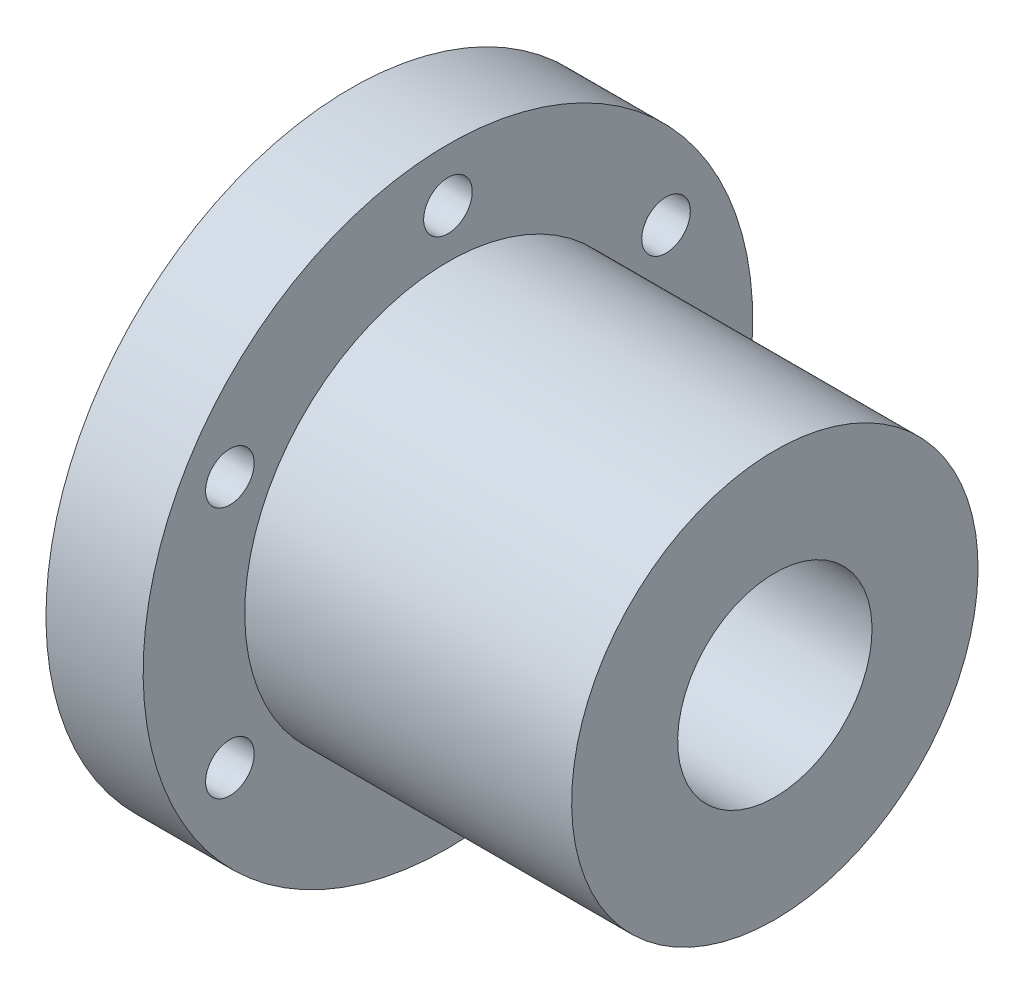
SolidWorks part; units mm, degrees
material "1.0037 (S235JR)"
ref_plane "Front Plane" through (0, 0, 0) normal (0, 0, 1) x (1, 0, 0)
ref_plane "Top Plane" through (0, 0, 0) normal (0, 1, 0) x (1, 0, 0)
ref_plane "Right Plane" through (0, 0, 0) normal (1, 0, 0) x (0, 0, -1)
sketch "Sketch1" plane through (0, 0, 0) normal (0, 0, 1) x (1, 0, 0)
  line L0 (-24, 34.5) -> (-13, 34.5)
  line L1 (-13, 34.5) -> (-13, 23)
  line L3 (24, 23) -> (24, 11)
  line L4 (24, 11) -> (-24, 11)
  line L5 (-24, 11) -> (-24, 34.5)
  line L9 (-13, 23) -> (24, 23)
  line L10 (-82.106, 0) -> (82.106, 0) construction
  point P12 (0, 11)
  dimension "D2" = 22
  dimension "D3" = 46
  dimension "D4" = 69
  dimension "D5" = 11
  dimension "L+1.5" = 48
  dimension "D7" = 37
revolve "Revolve1" add sketch "Sketch1" angle 360 about L10
sketch "Sketch2" plane through (-24, 0, 0) normal (-1, 0, 0) x (0, 0, 1)
  circle A0 centre (0, 0) radius 28.5 construction
  circle A1 centre (0, -28.5) radius 2.75
  dimension "D1" = 5.5
  dimension "D2" = 57
extrude "Cut-Extrude1" cut sketch "Sketch2" against normal up to next
sketch "Sketch3" plane through (-24, 0, 0) normal (-1, 0, 0) x (0, 0, 1)
  circle A0 centre (0, -28.5) radius 4.75
  dimension "D1" = 9.5
extrude "Cut-Extrude2" cut sketch "Sketch3" against normal blind 5.5
pattern_circular "CirPattern1" count 6 over 360 about axis through (0, 0, 0) along (1, 0, 0) of "Cut-Extrude1", "Cut-Extrude2"
